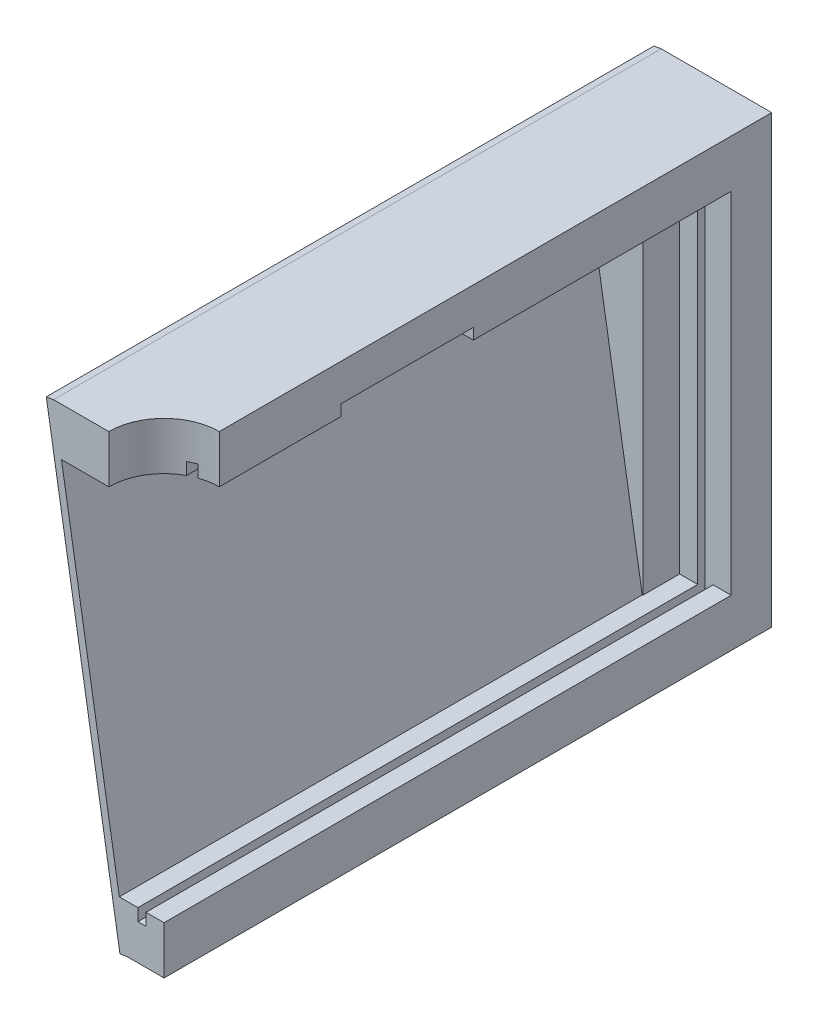
SolidWorks part; units mm, degrees
ref_plane "Front Plane" through (0, 0, 0) normal (0, 0, 1) x (1, 0, 0)
ref_plane "Top Plane" through (0, 0, 0) normal (0, 1, 0) x (1, 0, 0)
ref_plane "Right Plane" through (0, 0, 0) normal (1, 0, 0) x (0, 0, -1)
sketch "Sketch2" plane through (0, 0, 0) normal (1, 0, 0) x (0, 0, -1)
  line L0 (-34.1264, 9.1286) -> (-34.1264, -3.8714)
  line L1 (130.8736, 117.1286) -> (-34.1264, 117.1286)
  line L2 (130.8736, 117.1286) -> (130.8736, -3.8714)
  line L3 (130.8736, -3.8714) -> (-34.1264, -3.8714)
  line L4 (-34.1264, 117.1286) -> (-34.1264, 104.1286)
  line L5 (107.8736, 104.1286) -> (-34.1264, 104.1286)
  line L6 (107.8736, 104.1286) -> (107.8736, 9.1286)
  line L7 (107.8736, 9.1286) -> (-34.1264, 9.1286)
  dimension "D1" = 165
  dimension "D2" = 121
  dimension "D3" = 23
  dimension "D4" = 13
  dimension "D5" = 13
extrude "Boss-Extrude3" add sketch "Sketch2" along normal blind 40
sketch "Sketch4" plane through (0, 104.1286, 0) normal (0, -1, 0) x (1, 0, 0)
  line L0 (35, -107.8736) -> (35, 34.1264)
  line L1 (40, -107.8736) -> (0, -107.8736) construction
  line L2 (40, 34.1264) -> (0, 34.1264) construction
  line L3 (35, 34.1264) -> (33, 34.1264)
  line L4 (33, 34.1264) -> (33, -107.8736)
  line L5 (33, -107.8736) -> (35, -107.8736)
  line L6 (40, 34.1264) -> (40, -107.8736) construction
  dimension "D1" = 2
  dimension "D2" = 5
extrude "Cut-Extrude1" cut sketch "Sketch4" against normal blind 3
sketch "Sketch5" plane through (0, 0, -107.8736) normal (0, 0, 1) x (1, 0, 0)
  line L0 (33, 107.1286) -> (33, 9.1286)
  line L1 (40, 9.1286) -> (0, 9.1286) construction
  line L2 (33, 9.1286) -> (35, 9.1286)
  line L3 (35, 9.1286) -> (35, 107.1286)
  line L4 (35, 107.1286) -> (33, 107.1286)
  dimension "D1" = 2
extrude "Cut-Extrude2" cut sketch "Sketch5" against normal blind 3
sketch "Sketch6" plane through (0, 9.1286, 0) normal (0, 1, 0) x (1, 0, 0)
  line L0 (33, 110.8736) -> (35, 110.8736)
  line L1 (35, 110.8736) -> (35, -34.1264)
  line L2 (40, -34.1264) -> (0, -34.1264) construction
  line L3 (35, -34.1264) -> (33, -34.1264)
  line L4 (33, -34.1264) -> (33, 110.8736)
  dimension "D1" = 2
extrude "Cut-Extrude3" cut sketch "Sketch6" against normal blind 3
sketch "Sketch7" plane through (0, 0, -130.8736) normal (0, 0, -1) x (-1, 0, 0)
  line L0 (0, 117.1286) -> (0, -3.8714)
  line L1 (0, -3.8714) -> (-30, -3.8714)
  line L2 (-40, -3.8714) -> (0, -3.8714) construction
  line L3 (-30, -3.8714) -> (-10, 117.1286)
  line L4 (-40, 117.1286) -> (0, 117.1286) construction
  line L5 (-10, 117.1286) -> (0, 117.1286)
  dimension "D1" = 10
  dimension "D2" = 10
extrude "Cut-Extrude4" cut sketch "Sketch7" against normal blind 228
sketch "Sketch8" plane through (28.5793, 4.7239, 0) normal (-0.9866, -0.1631, 0) x (0, 0, 1)
  line L0 (-130.8736, 113.9299) -> (-130.8736, -8.7119)
  line L1 (-130.8736, -8.7119) -> (34.1264, -8.7119)
  line L2 (34.1264, -8.7119) -> (34.1264, 113.9299)
  line L3 (34.1264, 113.9299) -> (-130.8736, 113.9299)
extrude "Boss-Extrude5" add sketch "Sketch8" along normal blind 2
sketch "Sketch11" plane through (0, 0, 34.1264) normal (0, 0, 1) x (1, 0, 0)
  line L0 (33, 107.1286) -> (33, 107.4286)
  line L1 (33, 107.4286) -> (35, 107.4286)
  line L2 (35, 107.4286) -> (35, 107.1286)
  line L3 (35, 107.1286) -> (33, 107.1286)
  dimension "D1" = 0.3
extrude "Cut-Extrude5" cut sketch "Sketch11" against normal blind 145
sketch "Sketch12" plane through (0, 0, 34.1264) normal (0, 0, 1) x (1, 0, 0)
  line L0 (33, 6.1286) -> (35, 6.1286)
  line L1 (35, 6.1286) -> (35, 5.8286)
  line L2 (35, 5.8286) -> (33, 5.8286)
  line L3 (33, 5.8286) -> (33, 6.1286)
  dimension "D1" = 0.3
extrude "Cut-Extrude6" cut sketch "Sketch12" against normal blind 145
sketch "Sketch16" plane through (0, 0, 34.1264) normal (0, 0, 1) x (1, 0, 0)
  line L0 (33, 107.4286) -> (35, 107.4286)
  line L1 (35, 107.4286) -> (35, 5.8286)
  line L2 (35, 5.8286) -> (33, 5.8286)
  line L3 (33, 5.8286) -> (33, 107.4286)
extrude "Cut-Extrude7" cut sketch "Sketch16" against normal blind 154
sketch "Sketch17" plane through (40, 0, 0) normal (1, 0, 0) x (0, 0, -1)
  line L0 (107.8736, 104.1286) -> (117.8736, 104.1286)
  line L1 (107.8736, 9.1286) -> (117.8736, 9.1286)
  line L2 (117.8736, 9.1286) -> (117.8736, 104.1286)
  line L3 (107.8736, 104.1286) -> (107.8736, 9.1286)
extrude "Cut-Extrude9" cut sketch "Sketch17" against normal blind 12
sketch "Sketch18" plane through (0, 104.1286, 0) normal (0, -1, 0) x (1, 0, 0)
  line L0 (33, 34.1264) -> (28, 34.1264)
  line L1 (33, 34.1264) -> (12.1488, 34.1264) construction
  line L2 (28, 34.1264) -> (28, 29.1264)
  line L3 (28, 29.1264) -> (33, 29.1264)
  line L4 (33, 34.1264) -> (33, -117.8736) construction
  line L5 (33, 29.1264) -> (33, 34.1264)
extrude "Cut-Extrude10" cut sketch "Sketch18" against normal blind 56
sketch "Sketch19" plane through (40, 0, 0) normal (1, 0, 0) x (0, 0, -1)
  line L0 (13.8736, 107.1286) -> (49.8736, 107.1286)
  line L1 (-34.1264, 104.1286) -> (107.8736, 104.1286) construction
  line L2 (13.8736, 104.1286) -> (13.8736, 107.1286)
  line L3 (49.8736, 107.1286) -> (49.8736, 104.1286)
  line L4 (-34.1264, 104.1286) -> (117.8736, 104.1286) construction
  line L5 (49.8736, 104.1286) -> (13.8736, 104.1286)
  dimension "D1" = 36
  dimension "D2" = 3
extrude "Cut-Extrude11" cut sketch "Sketch19" against normal blind 6
sketch "Sketch20" plane through (0, 117.1286, 0) normal (0, 1, 0) x (1, 0, 0)
  line L0 (40, -34.1264) -> (25, -34.1264)
  line L1 (40, -34.1264) -> (40, -19.1264)
  circle A0 centre (40, -34.1264) radius 15
  line M1 (28, -29.1264) -> (33, -29.1264)
  line M2 (33, -29.1264) -> (33, -34.1264)
  line M3 (33, -34.1264) -> (40, -34.1264)
  line M4 (40, -34.1264) -> (40, 130.8736)
  line M7 (10, -34.1264) -> (28, -34.1264)
  line M8 (28, -34.1264) -> (28, -29.1264)
extrude "Cut-Extrude13" cut sketch "Sketch20" against normal blind 27 contours A0 M4 M7 M8 M1 M2 M3
sketch "Sketch22" plane through (40, 0, 0) normal (1, 0, 0) x (0, 0, -1)
  line L0 (117.8736, 104.1286) -> (119.8736, 104.1286)
  line L1 (119.8736, 104.1286) -> (119.8736, 9.1286)
  line L2 (119.8736, 9.1286) -> (117.8736, 9.1286)
  line L3 (117.8736, 9.1286) -> (117.8736, 104.1286)
  dimension "D1" = 95
  dimension "D2" = 2
extrude "Cut-Extrude22" cut sketch "Sketch22" against normal blind 5
sketch "Sketch23" plane through (0, 0, 34.1264) normal (0, 0, 1) x (1, 0, 0)
  line L0 (33, 5.8286) -> (35, 5.8286)
  line L1 (33, 107.4286) -> (35, 107.4286)
  line L2 (35, 5.8286) -> (35.1, 5.8286)
  line L3 (33, 5.8286) -> (32.9, 5.8286)
  line L4 (33, 107.4286) -> (32.9, 107.4286)
  line L5 (35, 107.4286) -> (35.1, 107.4286)
  line L6 (32.9, 107.4286) -> (32.9, 5.8286)
  line L7 (35.1, 5.8286) -> (35.1, 107.4286)
extrude "Cut-Extrude23" cut sketch "Sketch23" against normal blind 154
